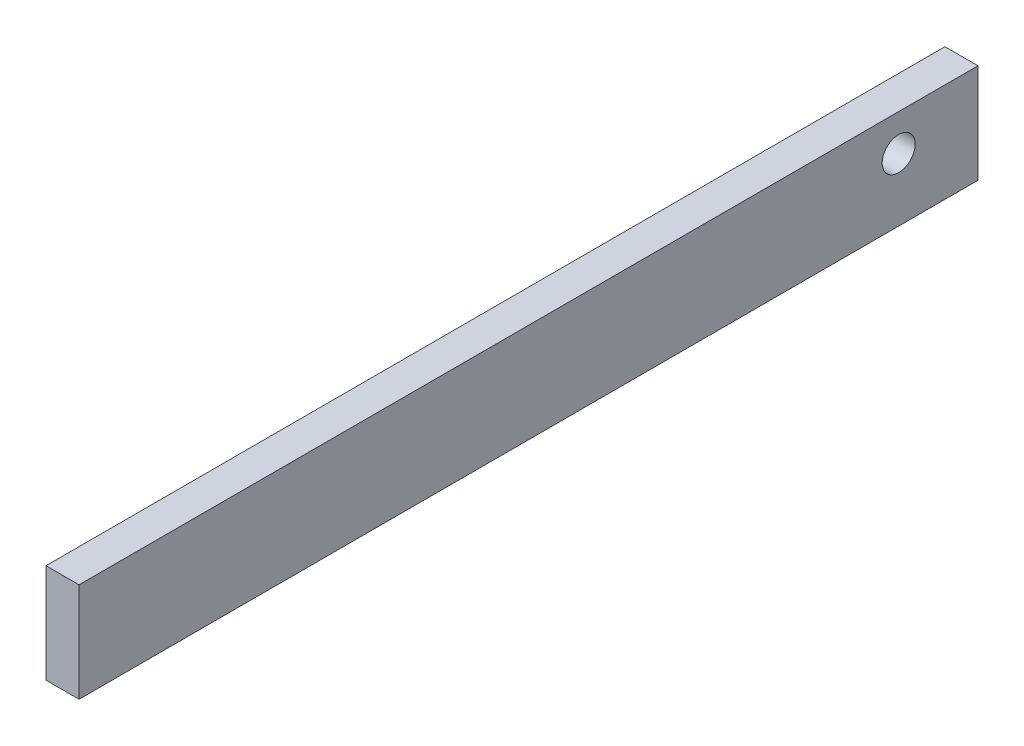
SolidWorks part; units mm, degrees
other "Markup1"
sketch "Sketch6" plane through (0, 0, 0) normal (0.1266, -0.8901, -0.4379) x (-0.2811, -0.4555, 0.8447)
ref_plane "Front Plane" through (0, 0, 0) normal (0, 0, 1) x (1, 0, 0)
ref_plane "Top Plane" through (0, 0, 0) normal (0, 1, 0) x (1, 0, 0)
ref_plane "Right Plane" through (0, 0, 0) normal (1, 0, 0) x (0, 0, -1)
sketch "Sketch1" plane through (0, 0, 0) normal (0, 0, 1) x (1, 0, 0)
  line L0 (0, 0) -> (-6.35, 0)
  line L3 (-6.35, 0) -> (-6.35, 19.05)
  line L4 (-6.35, 19.05) -> (0, 19.05)
  line L5 (0, 19.05) -> (0, 0)
  dimension "D1" = 19.05
  dimension "D4" = 6.35
extrude "Boss-Extrude1" add sketch "Sketch1" along normal blind 172.72
sketch "Sketch2" plane through (0, 19.05, 0) normal (0, 1, 0) x (1, 0, 0)
  line L0 (-3.175, 0) -> (-3.175, -172.72) construction
  line L3 (-6.35, 0) -> (0, 0) construction
  line L4 (-6.35, -172.72) -> (0, -172.72) construction
  circle A0 centre (-3.175, -166.37) radius 2.54
  circle A1 centre (-3.175, -6.35) radius 2.54
  dimension "D1" = 5.08
  dimension "D2" = 6.35
  dimension "D3" = 6.35
sketch "Sketch3" plane through (0, 0, 0) normal (0, -1, 0) x (1, 0, 0)
  line L0 (-3.175, 0) -> (-3.175, 172.72) construction
  line L3 (0, 172.72) -> (0, 0) construction
  line L4 (0, 0) -> (-6.35, 0) construction
  line L5 (0, 172.72) -> (-6.35, 172.72) construction
  circle A0 centre (-3.175, 166.37) radius 2.54
  circle A1 centre (-3.175, 6.35) radius 2.54
  dimension "D2" = 5.08
  dimension "D1" = 3.175
  dimension "D3" = 6.35
  dimension "D4" = 6.35
sketch "Sketch4" plane through (0, 0, 0) normal (1, 0, 0) x (0, 0, -1)
  line L0 (0, 19.05) -> (0, 0) construction
  line L3 (-172.72, 19.05) -> (0, 19.05) construction
  circle A0 centre (-15.24, 12.065) radius 3.175
  dimension "D3" = 6.35
  dimension "D1" = 15.24
  dimension "D2" = 6.985
extrude "Cut-Extrude3" cut sketch "Sketch4" against normal blind 25.4
sketch "Sketch5" plane through (0, 0, 172.72) normal (0, 0, 1) x (1, 0, 0)
  line L1 (-6.35, 0) -> (-12.7, 0)
  line L2 (-6.35, 0) -> (-6.35, 6.35)
  line L3 (-6.35, 6.35) -> (-12.7, 6.35)
  line L4 (-12.7, 0) -> (-12.7, 6.35)
  dimension "D1" = 6.35
  dimension "D2" = 6.35
